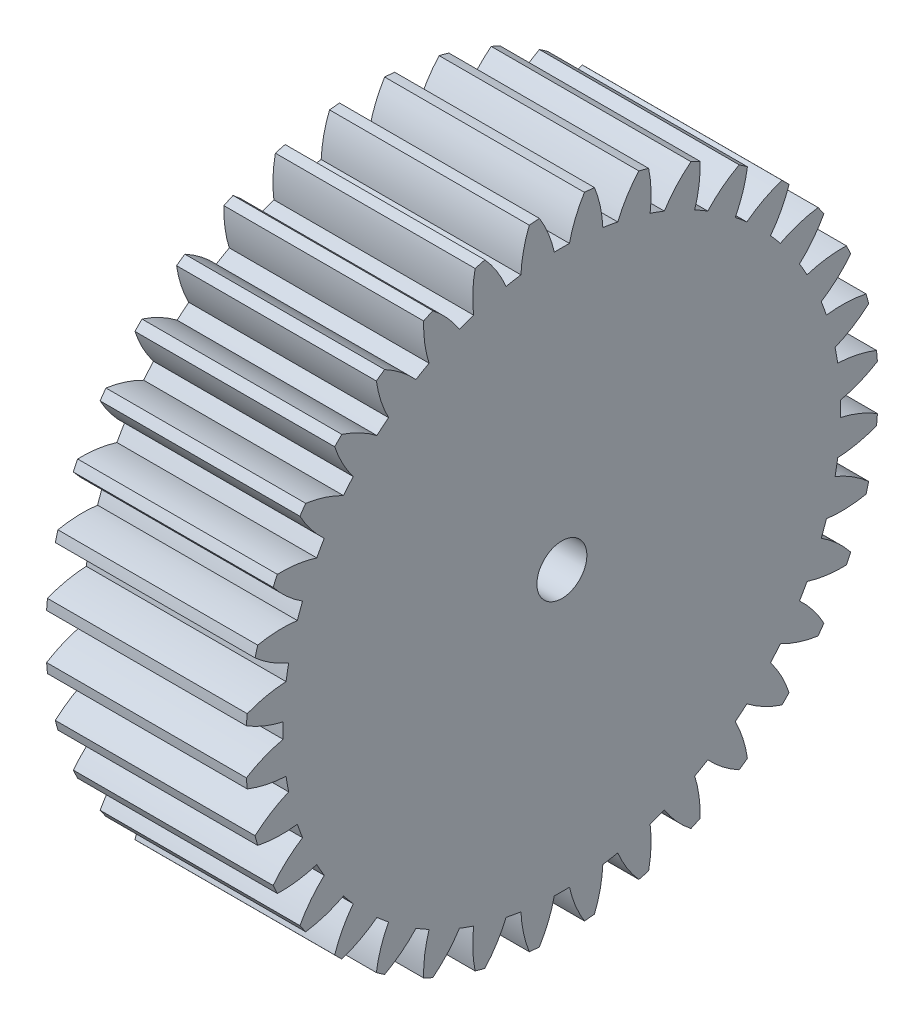
SolidWorks part; units mm, degrees
ref_plane "Plane1" through (0, 0, 0) normal (0, 0, 1) x (1, 0, 0)
ref_plane "Plane2" through (0, 0, 0) normal (0, 1, 0) x (1, 0, 0)
ref_plane "Plane3" through (0, 0, 0) normal (1, 0, 0) x (0, 0, -1)
sketch "HoldingSke" plane through (0, 0, 0) normal (0, 1, 0) x (1, 0, 0)
  line L0 (0, 0) -> (0.809, -0.5878)
  line L1 (-15, 0) -> (100, 0) construction
  line L2 (0, 0) -> (-2.1039, 2.3779)
  line L3 (0, 0) -> (-11.863, 4.5341)
  line L4 (0, 0) -> (6.9867, 5.0761)
  line L5 (0, 0) -> (-46.8476, -17.4728)
  line L6 (0, 0) -> (-9.9476, -6.7116)
  line L7 (-2.1039, 2.3779) -> (8.6586, 51.2059)
  line L8 (-76.2, 54.61) -> (-75.7, 54.61)
  line L9 (-71.009, 38.7566) -> (-53.1078, 45.2721)
  line L10 (-76.2, 71.12) -> (104.1128, 71.12)
  line L11 (0, 0) -> (-12, 0)
  line L12 (-76.2, 101.6) -> (-76.162, 101.6)
  line L13 (24.9733, 27.94) -> (52.9518, 28.4284)
  line L14 (24.9733, 27.94) -> (24.9743, 27.94)
  line L15 (24.9733, 27.94) -> (100.4006, 29.5858)
  line L16 (-63.627, -1) -> (-12.827, -1)
  circle A0 centre (0, 0) radius 1.5
  circle A1 centre (0, 0) radius 16.749
  circle A2 centre (0, 0) radius 37.5
  circle A3 centre (0, 0) radius 1.5
  dimension "MHD" = 33.498
  dimension "Hub_dia" = 75
  dimension "Bore" = 3
  dimension "MBD" = 3
  dimension "Num_teeth" = 36
  dimension "Pitch_radius" = 180.3128
  dimension "Pitch" = 1
  dimension "Width" = 12
  dimension "Overall_len" = 50
  dimension "Show_teeth" = 36
  dimension "Thickness" = 12
  dimension "OAL" = 50.0001
  dimension "T_dim" = 0.5
  dimension "Ap" = 20
  dimension "H" = 19.05
  dimension "Backlash" = 0.038
  dimension "Addendum_fac" = 1
  dimension "Dedendum_fac" = 1.25
  dimension "Clearance_fac" = 0.25
  dimension "Dedendum_add" = 0.001
  dimension "Module" = 1
sketch "BasProSke" plane through (0, 0, 0) normal (0, 1, 0) x (1, 0, 0)
  line L0 (-10, 0) -> (60, 0) construction
  line L1 (0, 0) -> (0, 19)
  line L2 (0, 0) -> (12, 0)
  line L3 (12, 0) -> (12, 19)
  line L4 (12, 19) -> (0, 19)
  dimension "Diameter" = 38
  dimension "Thickness" = 12
revolve "Base-Revolve" add sketch "BasProSke" angle 360 about L0
sketch "TooCutSke" plane through (0, 0, 0) normal (1, 0, 0) x (0, 0, -1)
  line L1 (0, 0) -> (0, 107) construction
  line L2 (0, 0) -> (-0.8516, 17.9798) construction
  line L3 (0, 0) -> (-3.1351, 35.8344) construction
  line L4 (-0.8516, 17.9798) -> (-1.5676, 17.9172) construction
  arc A0 (0.4547, 16.7428) -> (-0.4547, 16.7428) centre (0, 0) ccw
  arc A1 (1.3689, 18.9761) -> (-1.3689, 18.9761) centre (0, 0) ccw
  circle A2 centre (0, 0) radius 18 construction
  circle A3 centre (0, 0) radius 16.9145 construction
  arc A4 (-0.4547, 16.7428) -> (-1.3689, 18.9761) centre (-7.4808, 15.1702) ccw
  arc A5 (1.3689, 18.9761) -> (0.4547, 16.7428) centre (7.4808, 15.1702) ccw
  dimension "Root_dia" = 33.498
  dimension "Overcut_dia" = 38.0508
  dimension "Pitch_dia" = 36
  dimension "Base_dia" = 33.8289
  dimension "Flank_rad" = 7.2
  dimension "Half_ang" = 5
  dimension "Half_CT" = 0.7186
extrude "ToothCut" cut sketch "TooCutSke" along normal through all
fillet "Breaks" [suppressed] radius 0.02
fillet "RootFillets" [suppressed] radius 0.251
pattern_circular "TeethCuts" count 36 every 10 about axis through (-10, 0, 0) along (1, 0, 0) of "ToothCut", "RootFillets", "Breaks"
sketch "HubNeaOneSke" plane through (0, 0, 0) normal (-1, 0, 0) x (0, 0, 1)
  circle A0 centre (0, 0) radius 16.749
  dimension "Diameter" = 33.498
extrude "HubNearOne" [suppressed] add sketch "HubNeaOneSke" along normal blind 38.0001
sketch "HubNeaBotSke" plane through (0, 0, 0) normal (-1, 0, 0) x (0, 0, 1)
  circle A0 centre (0, 0) radius 16.749
  dimension "Diameter" = 33.498
extrude "HubNearBoth" [suppressed] add sketch "HubNeaBotSke" along normal blind 19
ref_plane "FarPln" through (12, 0, 0) normal (1, 0, 0) x (0, 0, -1)
sketch "HubFarSke" plane through (12, 0, 0) normal (1, 0, 0) x (0, 0, -1)
  circle A0 centre (0, 0) radius 16.749
  dimension "Diameter" = 33.498
extrude "HubFar" [suppressed] add sketch "HubFarSke" along normal blind 19
sketch "BorSke" plane through (0, 0, 0) normal (1, 0, 0) x (0, 0, -1)
  circle A0 centre (0, 0) radius 1.5
  dimension "Diameter" = 3
extrude "Bore" cut sketch "BorSke" along normal mid plane 100.0001
sketch "KeySke" plane through (0, 0, 0) normal (1, 0, 0) x (0, 0, -1)
  line L0 (-0.6, 0) -> (-0.6, 2)
  line L1 (-0.6, 2) -> (0.6, 2)
  line L2 (0.6, 2) -> (0.6, 0)
  line L3 (0, 0) -> (0, 34) construction
  line L4 (-0.6, 0) -> (0.6, 0)
  dimension "Offset" = 2
  dimension "Width" = 1.2
extrude "Keyway" [suppressed] cut sketch "KeySke" along normal mid plane 100.0001
pattern_circular "Keyway2" [suppressed] count 2 every 90 about axis through (-10, 0, 0) along (1, 0, 0)
equation "' \"Module@HoldingSke\" = 6.35"
equation "' \"Num_teeth@HoldingSke\" = 12"
equation "' \"Ap@HoldingSke\" =  20"
equation "' \"Width@HoldingSke\" = 0.5 * 25.4"
equation "' \"Hub_dia@HoldingSke\"= 1 * 25.4"
equation "' \"Overall_len@HoldingSke\" = 1.0 * 25.4"
equation "' \"Bore@HoldingSke\" = 0.75 * 25.4"
equation "' \"T_dim@HoldingSke\" = 0.1 * 25.4"
equation "' \"Width@KeySke\" = 0.25 * 25.4"
equation "' \"Show_teeth@HoldingSke\" = 13"
equation "' \"Backlash@HoldingSke\" = 0.009 * 25.4"
equation "' \"Addendum_fac@HoldingSke\" = 1.0"
equation "' \"Dedendum_fac@HoldingSke\" = 1.25"
equation "' \"Dedendum_add@HoldingSke\" = 0.00005 * 25.4"
equation "' \"Clearance_fac@HoldingSke\" = 0.25"
equation "\"Pitch@HoldingSke\" = 1 / \"Module@HoldingSke\""
equation "\"Overcut_dia@TooCutSke\" = (\"Num_teeth@HoldingSke\" + 2 * \"Addendum_fac@HoldingSke\") / \"Pitch@HoldingSke\" + 0.002 * 25.4"
equation "\"Pitch_dia@TooCutSke\" = \"Num_teeth@HoldingSke\" / \"Pitch@HoldingSke\""
equation "\"Base_dia@TooCutSke\" = \"Num_teeth@HoldingSke\" / \"Pitch@HoldingSke\" * cos((\"Ap@HoldingSke\"  * 3.14159265 / 180))"
equation "\"Root_dia@TooCutSke\" = (\"Num_teeth@HoldingSke\" + 2) / \"Pitch@HoldingSke\" - 2 * (\"Addendum_fac@HoldingSke\" + \"Dedendum_fac@HoldingSke\") / \"Pitch@HoldingSke\" - \"Dedendum_add@HoldingSke\" * 2"
equation "\"Half_ang@TooCutSke\" = 180 / \"Num_teeth@HoldingSke\""
equation "\"Half_CT@TooCutSke\" = \"Num_teeth@HoldingSke\" / \"Pitch@HoldingSke\" * sin((3.14159265 / 2 / \"Num_teeth@HoldingSke\")) / 2 - 7 * \"Backlash@HoldingSke\" / 4"
equation "\"Flank_rad@TooCutSke\" = \"Num_teeth@HoldingSke\" / \"Pitch@HoldingSke\" / 5"
equation "\"Radius@RootFillets\" = \"Clearance_fac@HoldingSke\" / \"Pitch@HoldingSke\" + \"Dedendum_add@HoldingSke\""
equation "\"Break_rad@Breaks\" = 0.02 / \"Pitch@HoldingSke\""
equation "\"Thickness@HoldingSke\" = \"Width@HoldingSke\""
equation "\"OAL@HoldingSke\" = \"Thickness@HoldingSke\""
equation "\"MHD@HoldingSke\" = (\"Num_teeth@HoldingSke\" + 2) / \"Pitch@HoldingSke\" - 2 * (\"Addendum_fac@HoldingSke\" + \"Dedendum_fac@HoldingSke\")  / \"Pitch@HoldingSke\" - \"Dedendum_add@HoldingSke\" * 2"
equation "\"MBD@HoldingSke\" = (\"Num_teeth@HoldingSke\" + 2) / \"Pitch@HoldingSke\" - 2 * (\"Addendum_fac@HoldingSke\" + \"Dedendum_fac@HoldingSke\")  / \"Pitch@HoldingSke\" - \"Dedendum_add@HoldingSke\" * 2 - 0.002 * 25.4"
equation "\"MHD@HoldingSke\" = ((sgn( \"MHD@HoldingSke\" - \"Hub_dia@HoldingSke\" )-1)*( \"MHD@HoldingSke\" - \"Hub_dia@HoldingSke\" ))/-2+ \"Hub_dia@HoldingSke\""
equation "\"MBD@HoldingSke\" = ((sgn( \"MBD@HoldingSke\" - \"Bore@HoldingSke\" )-1)*( \"MBD@HoldingSke\" - \"Bore@HoldingSke\" ))/-2+ \"Bore@HoldingSke\""
equation "\"OAL@HoldingSke\" = ((sgn( \"OAL@HoldingSke\" - \"Overall_len@HoldingSke\" )+1)*( \"OAL@HoldingSke\" - \"Overall_len@HoldingSke\" ))/2 + \"Overall_len@HoldingSke\" + 0.000002 * 25.4"
equation "\"Num_teeth@TeethCuts\" = int( \"Show_teeth@HoldingSke\" ) + 1"
equation "\"Num_teeth@TeethCuts\" = ((sgn( \"Num_teeth@TeethCuts\" - \"Num_teeth@HoldingSke\" )-1)*( \"Num_teeth@TeethCuts\" - \"Num_teeth@HoldingSke\" ))/-2+ \"Num_teeth@HoldingSke\""
equation "\"Num_teeth@TeethCuts\" = ((sgn( \"Num_teeth@TeethCuts\" - 2.0)+1)*( \"Num_teeth@TeethCuts\" - 2.0))/2 +2.0"
equation "\"Angle@TeethCuts\" = 360.0 / \"Num_teeth@HoldingSke\""
equation "\"Diameter@BasProSke\" = (\"Num_teeth@HoldingSke\" + 2 * \"Addendum_fac@HoldingSke\") / \"Pitch@HoldingSke\""
equation "\"Thickness@BasProSke\"  = \"Thickness@HoldingSke\""
equation "' \"Fillet_rad@BasProSke\" =  \"Thickness@HoldingSke\" * 0.05"
equation "\"MHD@HoldingSke\" = ((sgn( \"MHD@HoldingSke\" - \"Root_dia@TooCutSke\" )-1)*( \"MHD@HoldingSke\" - \"Root_dia@TooCutSke\" ))/-2+ \"Root_dia@TooCutSke\""
equation "\"Diameter@HubNeaOneSke\" = \"MHD@HoldingSke\""
equation "\"Length@HubNearOne\" = \"OAL@HoldingSke\" - \"Thickness@BasProSke\""
equation "\"Diameter@HubNeaBotSke\" = \"MHD@HoldingSke\""
equation "\"Length@HubNearBoth\" = ( \"OAL@HoldingSke\" - \"Thickness@BasProSke\" ) / 2.0"
equation "\"Thickness@FarPln\" = \"Thickness@BasProSke\""
equation "\"Diameter@HubFarSke\" = \"MHD@HoldingSke\""
equation "\"Length@HubFar\" = ( \"OAL@HoldingSke\" - \"Thickness@BasProSke\" ) / 2.0"
equation "\"Diameter@BorSke\" = \"MBD@HoldingSke\""
equation "\"D1@Bore\" = \"OAL@HoldingSke\" * 2.0"
equation "\"D1@Keyway\" = \"OAL@HoldingSke\" * 2.0"
equation "\"Offset@KeySke\" = \"T_dim@HoldingSke\" + \"MBD@HoldingSke\" / 2.0"
